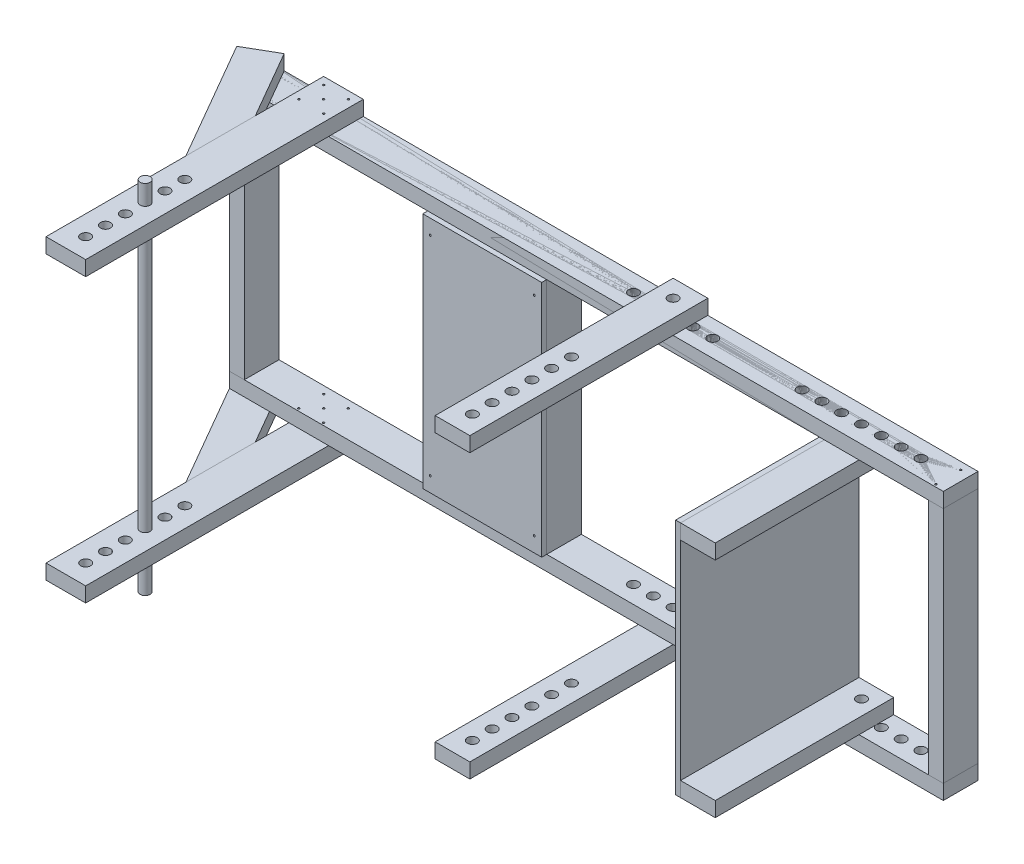
SolidWorks part; units mm, degrees
material "Custom Plastic"
ref_plane "X-Y Datum" through (0, 0, 0) normal (0, 0, 1) x (1, 0, 0)
ref_plane "X-Z Datum" through (0, 0, 0) normal (0, 1, 0) x (1, 0, 0)
ref_plane "Y-Z Datum" through (0, 0, 0) normal (1, 0, 0) x (0, 0, -1)
sketch "Sketch1" plane through (0, 0, 0) normal (0, 0, 1) x (1, 0, 0)
  line L1 (0, 0) -> (1828.8, 0)
  line L2 (0, 0) -> (0, -38.1)
  line L3 (0, -38.1) -> (1828.8, -38.1)
  line L4 (1828.8, 0) -> (1828.8, -38.1)
  dimension "D1" = 38.1
  dimension "D2" = 1828.8
extrude "Boss-Extrude1" add sketch "Sketch1" against normal blind 88.9
sketch "Sketch2" plane through (0, 0, 0) normal (0, 1, 0) x (1, 0, 0)
  line L0 (1828.8, 88.9) -> (0, 88.9) construction
  line L1 (1828.8, 0) -> (1790.7, 0)
  line L2 (1828.8, 0) -> (1828.8, 88.9)
  line L3 (1828.8, 88.9) -> (1790.7, 88.9)
  line L4 (1790.7, 0) -> (1790.7, 88.9)
  line L5 (1828.8, 0) -> (0, 0) construction
  line L6 (0, 0) -> (38.1, 0)
  line L7 (0, 0) -> (0, 88.9)
  line L8 (0, 88.9) -> (38.1, 88.9)
  line L9 (38.1, 0) -> (38.1, 88.9)
  line L10 (546.1, 0) -> (508, 0)
  line L11 (546.1, 0) -> (546.1, 88.9)
  line L12 (546.1, 88.9) -> (508, 88.9)
  line L13 (508, 0) -> (508, 88.9)
  line L15 (812.8, 0) -> (774.7, 0)
  line L16 (812.8, 0) -> (812.8, 88.9)
  line L17 (812.8, 88.9) -> (774.7, 88.9)
  line L18 (774.7, 0) -> (774.7, 88.9)
  dimension "D1" = 38.1
  dimension "D2" = 508
  dimension "D3" = 304.8
extrude "Boss-Extrude2" add sketch "Sketch2" along normal blind 609.6 separate body
sketch "Sketch3" plane through (0, 0, 0) normal (0, 0, 1) x (1, 0, 0)
  line L0 (0, 609.6) -> (0, 0) construction
  line L1 (1828.8, 609.6) -> (0, 609.6)
  line L2 (1828.8, 609.6) -> (1828.8, 647.7)
  line L3 (1828.8, 647.7) -> (0, 647.7)
  line L4 (0, 609.6) -> (0, 647.7)
  dimension "D1" = 38.1
extrude "Boss-Extrude3" add sketch "Sketch3" against normal blind 88.9 separate body
sketch "Sketch14" plane through (0, 647.7, 0) normal (0, 1, 0) x (1, 0, 0)
  line L0 (1676.4, 44.45) -> (1625.6, 44.45) construction
  line L1 (1625.6, 44.45) -> (1574.8, 44.45) construction
  line L2 (1574.8, 44.45) -> (1524, 44.45) construction
  line L3 (1524, 44.45) -> (1473.2, 44.45) construction
  line L4 (1473.2, 44.45) -> (1193.8, 44.45) construction
  line L5 (1193.8, 44.45) -> (1143, 44.45) construction
  line L6 (1143, 44.45) -> (1092.2, 44.45) construction
  line L7 (1092.2, 44.45) -> (1041.4, 44.45) construction
  line L8 (1041.4, 44.45) -> (990.6, 44.45) construction
  line L9 (1828.8, 88.9) -> (1828.8, 0) construction
  line L10 (1727.2, 44.45) -> (1676.4, 44.45) construction
  circle A0 centre (1676.4, 44.45) radius 12.7
  circle A1 centre (1625.6, 44.45) radius 12.7
  circle A2 centre (1574.8, 44.45) radius 12.7
  circle A3 centre (1524, 44.45) radius 12.7
  circle A4 centre (1473.2, 44.45) radius 12.7
  circle A5 centre (1193.8, 44.45) radius 12.7
  circle A6 centre (1143, 44.45) radius 12.7
  circle A7 centre (1092.2, 44.45) radius 12.7
  circle A8 centre (1041.4, 44.45) radius 12.7
  circle A9 centre (990.6, 44.45) radius 12.7
  circle A10 centre (1422.4, 44.45) radius 12.7
  circle A11 centre (1727.2, 44.45) radius 12.7
  point P24 (1828.8, 44.45)
  dimension "D11" = 25.4
  dimension "D12" = 50.8
  dimension "D1" = 50.8
  dimension "D2" = 50.8
  dimension "D3" = 50.8
  dimension "D4" = 50.8
  dimension "D5" = 50.8
  dimension "D6" = 50.8
  dimension "D7" = 50.8
  dimension "D8" = 50.8
  dimension "D9" = 254
  dimension "D10" = 736.6
  dimension "D13" = 50.8
extrude "Cut-Extrude3" cut sketch "Sketch14" against normal up to surface (685.8 mm away)
ref_plane "Plane1" through (0, 304.8, 0) normal (0, 1, 0) x (1, 0, 0)
sketch "Sketch4" plane through (0, 647.7, 0) normal (0, 1, 0) x (1, 0, 0)
  line L0 (1828.8, 88.9) -> (0, 88.9) construction
  line L1 (152.4, 88.9) -> (254, 88.9)
  line L2 (152.4, 88.9) -> (152.4, -622.3)
  line L3 (152.4, -622.3) -> (254, -622.3)
  line L4 (254, 88.9) -> (254, -622.3)
  line L5 (0, 88.9) -> (0, 0) construction
  line L7 (1136.65, 88.9) -> (1047.75, 88.9)
  line L8 (1136.65, 88.9) -> (1136.65, -520.7)
  line L9 (1136.65, -520.7) -> (1047.75, -520.7)
  line L10 (1047.75, 88.9) -> (1047.75, -520.7)
  line L11 (1828.8, 0) -> (0, 0) construction
  line L12 (749.3, 0) -> (508, 0) construction
  line L13 (749.3, 0) -> (749.3, -12.7) construction
  line L14 (749.3, -12.7) -> (508, -12.7) construction
  line L15 (508, 0) -> (508, -12.7) construction
  line L16 (508, -12.7) -> (100.0724, -595.2809) construction
  line L17 (100.0724, -595.2809) -> (89.6692, -587.9965) construction
  line L18 (89.6692, -587.9965) -> (497.5968, -5.4156) construction
  line L19 (497.5968, -5.4156) -> (508, -12.7) construction
  circle A0 centre (203.2, -571.5) radius 12.7
  circle A1 centre (203.2, -520.7) radius 12.7
  circle A2 centre (203.2, -469.9) radius 12.7
  circle A3 centre (203.2, -419.1) radius 12.7
  circle A6 centre (1092.2, -469.9) radius 12.7
  circle A8 centre (1092.2, -419.1) radius 12.7
  circle A9 centre (1092.2, -368.3) radius 12.7
  circle A10 centre (1092.2, -317.5) radius 12.7
  circle A11 centre (203.2, -368.3) radius 12.7
  circle A12 centre (203.2, -317.5) radius 12.7
  circle A13 centre (1092.2, -266.7) radius 12.7
  circle A14 centre (1092.2, -215.9) radius 12.7
  point P11 (203.2, -622.3)
  point P25 (1092.2, 88.9)
  point P26 (203.2, 88.9)
  point P30 (1092.2, -520.7)
  dimension "D4" = 25.4
  dimension "D11" = 25.4
  dimension "D1" = 101.6
  dimension "D2" = 711.2
  dimension "D3" = 152.4
  dimension "D5" = 50.8
  dimension "D7" = 50.8
  dimension "D8" = 88.9
  dimension "D9" = 609.6
  dimension "D10" = 889
  dimension "D12" = 50.8
  dimension "D14" = 50.8
  dimension "D15" = 241.3
  dimension "D16" = 12.7
  dimension "D17" = 12.7
  dimension "D18" = 125
  dimension "D19" = 711.2
  dimension "D20" = 508
  dimension "D6" = 6
  dimension "D13" = 6
extrude "Boss-Extrude4" add sketch "Sketch4" along normal blind 38.1 separate body
sketch "Sketch5" plane through (0, 0, 0) normal (0, 1, 0) x (1, 0, 0)
  line L0 (1828.8, 88.9) -> (0, 88.9) construction
  line L1 (1612.9, 88.9) -> (1524, 88.9)
  line L2 (1612.9, 88.9) -> (1612.9, -368.3)
  line L3 (1612.9, -368.3) -> (1524, -368.3)
  line L4 (1524, 88.9) -> (1524, -368.3)
  line L5 (1828.8, 88.9) -> (1828.8, 0) construction
  dimension "D1" = 88.9
  dimension "D2" = 457.2
  dimension "D3" = 304.8
extrude "Boss-Extrude6" add sketch "Sketch5" along normal blind 38.1
sketch "Sketch6" plane through (1524, 0, 0) normal (-1, 0, 0) x (0, 0, 1)
  line L0 (368.3, 38.1) -> (368.3, 0) construction
  line L1 (-88.9, 38.1) -> (-88.9, 0) construction
  circle A0 centre (330.2, 19.05) radius 2.413
  circle A1 centre (139.7, 19.05) radius 2.413
  circle A2 centre (-50.8, 19.05) radius 2.413
  point P9 (368.3, 19.05)
  dimension "D1" = 4.826
  dimension "D2" = 38.1
  dimension "D3" = 190.5
  dimension "D4" = 38.1
extrude "Cut-Extrude1" cut sketch "Sketch6" against normal blind 25.4
mirror "Mirror4" about plane through (0, 304.8, 0) normal (0, 1, 0) of bodies 106 109 115
sketch "Sketch7" plane through (1524, 0, 0) normal (-1, 0, 0) x (0, 0, 1)
  line L1 (368.3, 0) -> (-88.9, 0)
  line L2 (368.3, 0) -> (368.3, 609.6)
  line L3 (368.3, 609.6) -> (-88.9, 609.6)
  line L4 (-88.9, 0) -> (-88.9, 609.6)
  circle A0 centre (330.2, 590.55) radius 2.413
  circle A1 centre (139.7, 590.55) radius 2.413
  circle A2 centre (330.2, 19.05) radius 2.413
  circle A3 centre (139.7, 19.05) radius 2.413
  circle A4 centre (-50.8, 19.05) radius 2.413
  dimension "D1" = 4.826
extrude "Boss-Extrude7" add sketch "Sketch7" along normal blind 12.7 separate body
ref_plane "Plane2" through (0, 736.6, 0) normal (0, 1, 0) x (1, 0, 0)
sketch "Sketch11" plane through (0, 736.6, 0) normal (0, 1, 0) x (1, 0, 0)
  circle A1 centre (203.2, -419.1) radius 12.7
  dimension "D1" = 25.4
extrude "Boss-Extrude9" add sketch "Sketch11" against normal blind 914.4 separate body
sketch "Sketch12" plane through (0, 0, 0) normal (0, 0, 1) x (1, 0, 0)
  line L1 (812.8, 0) -> (508, 0)
  line L2 (812.8, 0) -> (812.8, 609.6)
  line L3 (812.8, 609.6) -> (508, 609.6)
  line L4 (508, 0) -> (508, 609.6)
extrude "Boss-Extrude11" add sketch "Sketch12" along normal blind 12.7 separate body
sketch "Sketch15" plane through (0, 685.8, 0) normal (0, 1, 0) x (1, 0, 0)
  circle A0 centre (1574.8, 44.45) radius 12.7
  circle A1 centre (1092.2, 44.45) radius 12.7
  circle A2 centre (1092.2, 44.45) radius 12.7 construction
  dimension "D1" = 25.4
  dimension "D2" = 25.4
extrude "Cut-Extrude4" cut sketch "Sketch15" against normal up to surface (762 mm away) up to face at (1092.2, -76.2, 215.9)
sketch "Sketch16" plane through (0, 685.8, 0) normal (0, 1, 0) x (1, 0, 0)
  line L0 (254, -622.3) -> (254, 88.9) construction
  line L1 (152.4, 88.9) -> (254, 88.9) construction
  line L2 (152.4, 88.9) -> (152.4, -12.7) construction
  line L3 (152.4, -12.7) -> (254, -12.7) construction
  line L4 (254, 88.9) -> (254, -12.7) construction
  line L5 (152.4, -12.7) -> (254, 88.9) construction
  line L6 (254, -12.7) -> (152.4, 88.9) construction
  line L7 (0, 88.9) -> (0, 0) construction
  line L8 (1828.8, 88.9) -> (1828.8, 0) construction
  circle A0 centre (234.95, 6.35) radius 2.413
  circle A1 centre (171.45, 6.35) radius 2.413
  circle A2 centre (234.95, 69.85) radius 2.413
  circle A3 centre (171.45, 69.85) radius 2.413
  circle A4 centre (203.2, 38.1) radius 2.413
  circle A5 centre (25.4, 6.35) radius 2.413
  circle A6 centre (25.4, 69.85) radius 2.413
  circle A7 centre (1803.4, 6.35) radius 2.413
  circle A8 centre (1803.4, 69.85) radius 2.413
  point P9 (203.2, 38.1)
  dimension "D1" = 4.826
  dimension "D4" = 19.05
  dimension "D2" = 19.05
  dimension "D3" = 19.05
  dimension "D5" = 19.05
  dimension "D6" = 25.4
  dimension "D7" = 25.4
extrude "Cut-Extrude7" cut sketch "Sketch16" against normal blind 152.4
mirror "Mirror5" about plane through (0, 304.8, 0) normal (0, 1, 0) of "Cut-Extrude7"
sketch "Sketch17" plane through (0, 0, 12.7) normal (0, 0, 1) x (1, 0, 0)
  line L0 (774.7, 609.6) -> (812.8, 609.6) construction
  line L1 (508, 609.6) -> (546.1, 609.6) construction
  line L2 (1524, 0) -> (0, 0) construction
  line L3 (1524, 609.6) -> (0, 609.6) construction
  circle A0 centre (793.75, 38.1) radius 2.413
  circle A1 centre (527.05, 38.1) radius 2.413
  circle A2 centre (793.75, 571.5) radius 2.413
  circle A3 centre (527.05, 571.5) radius 2.413
  point P12 (793.75, 609.6)
  point P17 (527.05, 609.6)
  dimension "D3" = 4.826
  dimension "D1" = 38.1
  dimension "D2" = 38.1
extrude "Cut-Extrude8" cut sketch "Sketch17" against normal blind 50.8 and the other way blind 50.8
sketch "Sketch18" plane through (0, 685.8, 0) normal (0, 1, 0) x (1, 0, 0)
  line L0 (152.4, -263.9645) -> (152.4, -86.1645)
  line L1 (152.4, 88.9) -> (152.4, -622.3) construction
  line L2 (152.4, -86.1645) -> (51.3264, 88.9)
  line L3 (51.3264, 88.9) -> (-25.6632, 44.45)
  line L4 (-25.6632, 44.45) -> (152.4, -263.9645)
  line L6 (1828.8, 88.9) -> (0, 88.9) construction
  dimension "D1" = 88.9
  dimension "D2" = 60
extrude "Boss-Extrude12" add sketch "Sketch18" against normal blind 38.1 separate body
mirror "Mirror7" about plane through (0, 304.8, 0) normal (0, 1, 0) of bodies 157
ref_plane "Plane3" through (1092.2, 0, 0) normal (-1, 0, 0) x (0, 0, 1)
